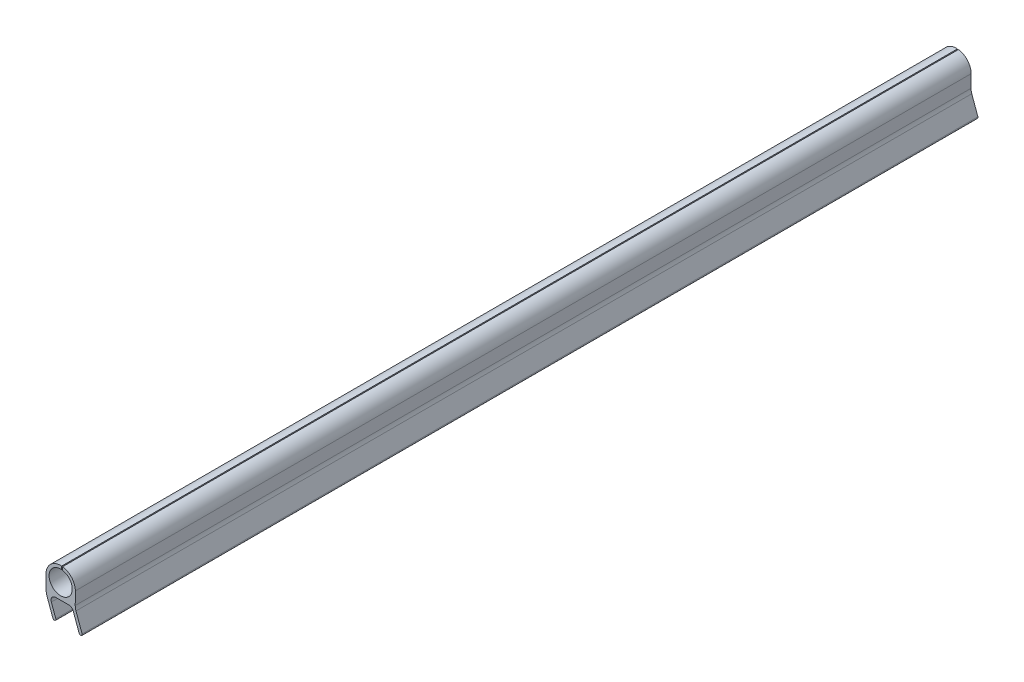
SolidWorks part; units mm, degrees
material "PVC 0.007 Plasticized"
ref_plane "Front Plane" through (0, 0, 0) normal (0, 0, 1) x (1, 0, 0)
ref_plane "Top Plane" through (0, 0, 0) normal (0, 1, 0) x (1, 0, 0)
ref_plane "Right Plane" through (0, 0, 0) normal (1, 0, 0) x (0, 0, -1)
sketch "Sketch3" plane through (0, 0, 0) normal (0, 0, 1) x (1, 0, 0)
  line L1 (-6.0346, -14.0261) -> (-3.1486, -21.9553)
  line L2 (-3.2156, -10) -> (5.2979, -10)
  line L3 (8.1169, -11.9739) -> (11.9988, -22.6393)
  line L4 (-9.5, 0) -> (-9.5, -8.2367)
  line L5 (-8.7763, -12.341) -> (-5.028, -22.6393)
  line L6 (0.5025, 7.4831) -> (0.6365, 9.4787)
  line L9 (1, 7.433) -> (1.2667, 9.4152)
  line L12 (9.5, 0) -> (9.4252, -8.2364)
  line L13 (9.9073, -11.0452) -> (13.8782, -21.9553)
  line L14 (8.0279, -11.7293) -> (11.9988, -22.6393) construction
  line L15 (-6.8969, -11.6569) -> (-3.1486, -21.9553) construction
  line L18 (-7.5, 0) -> (-7.5, -8.2367) construction
  line L19 (-9.5, 0) -> (9.5, 0) construction
  arc A0 (0.5025, 7.4831) -> (-7.5, 0) centre (0, 0) ccw
  arc A1 (7.5, 0) -> (1, 7.433) centre (0, 0) ccw
  arc A4 (7.5, 0) -> (-7.5, 0) centre (0, 0) cw
  arc A6 (0.6365, 9.4787) -> (-9.5, 0) centre (0, 0) ccw
  arc A7 (-9.5, -8.2367) -> (-8.7763, -12.341) centre (2.5, -8.2367) ccw
  arc A8 (9.5, 0) -> (1.2667, 9.4152) centre (0, 0) ccw
  arc A9 (9.4252, -8.2364) -> (9.9073, -11.0452) centre (17.4248, -8.3091) ccw
  arc A10 (-7.5, -8.2367) -> (-6.8969, -11.6569) centre (2.5, -8.2367) ccw construction
  arc A11 (5.2979, -10) -> (8.1169, -11.9739) centre (5.2979, -13) cw
  arc A12 (-3.2156, -10) -> (-6.0346, -14.0261) centre (-3.2156, -13) ccw
  arc A13 (-3.1486, -21.9553) -> (-5.028, -22.6393) centre (-4.0883, -22.2973) cw
  arc A14 (11.9988, -22.6393) -> (13.8782, -21.9553) centre (12.9385, -22.2973) ccw
  point P18 (-7.5, -10)
  point P38 (0, -7.5)
  dimension "D1" = 15
  dimension "D7" = 14
  dimension "D8" = 8.2367
  dimension "D12" = 12
  dimension "D14" = 8
  dimension "D3" = 3
  dimension "D13" = 2.5
  dimension "D2" = 10
  dimension "D4" = 160
  dimension "D5" = 0.5
  dimension "D6" = 1
  dimension "D11" = 8.2367
  dimension "D15" = 11.6102
  dimension "D9" = 2
  dimension "D10" = 2
extrude "Boss-Extrude1" add sketch "Sketch3" against normal blind 580 contours A4 A0 L6 A6 L4 A7 L5 A13 L1 A12 L2 A11 L3 A14 L13 A9 L12 A8 L9 A1
